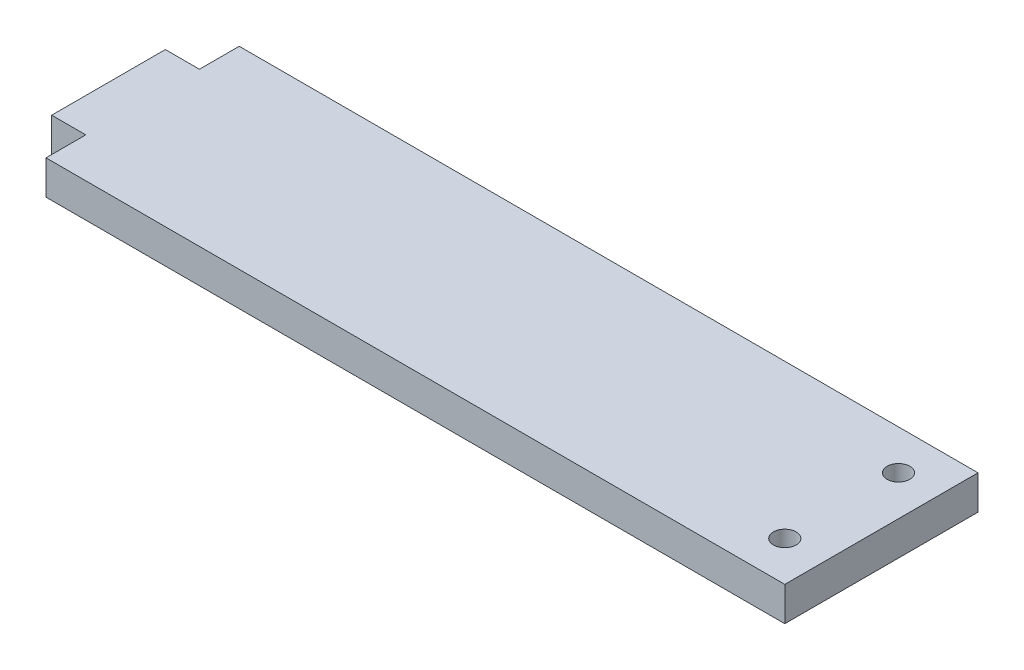
SolidWorks part; units mm, degrees
material "PVC rigide"
ref_plane "Plan de face" through (0, 0, 0) normal (0, 0, 1) x (1, 0, 0)
ref_plane "Plan de dessus" through (0, 0, 0) normal (0, 1, 0) x (1, 0, 0)
ref_plane "Plan de droite" through (0, 0, 0) normal (1, 0, 0) x (0, 0, -1)
sketch "Esquisse2" plane through (0, 0, 0) normal (0, 1, 0) x (1, 0, 0)
  line L0 (-353.8895, 0) -> (-217.8895, 0) construction
  line L1 (-347.8895, 17) -> (-217.8895, 17)
  line L2 (-353.8895, 10) -> (-353.8895, -10)
  line L3 (-282.8895, 17) -> (-282.8895, -17) construction
  line L4 (-347.8895, -10) -> (-347.8895, -17)
  line L5 (-353.8895, 10) -> (-347.8895, 10)
  line L6 (-353.8895, -10) -> (-347.8895, -10)
  line L7 (-347.8895, -17) -> (-217.8895, -17)
  line L8 (-347.8895, 10) -> (-347.8895, 17)
  line L9 (-217.8895, 17) -> (-217.8895, -17)
  point P0 (0, 0)
  point P11 (-282.8895, 0)
  dimension "D1" = 10
  dimension "D2" = 7
  dimension "D3" = 130
  dimension "D4" = 6
extrude "Boss.-Extru.1" add sketch "Esquisse2" along normal blind 6
sketch "Esquisse3" plane through (-347.8895, 0, 0) normal (-1, 0, 0) x (0, 0, 1)
  line L0 (-17, 3) -> (-10, 3) construction
  line L1 (-17, 6) -> (-17, 0) construction
  line L2 (-10, 6) -> (-10, 0) construction
  line L3 (10, 3) -> (17, 3) construction
  line L4 (10, 6) -> (10, 0) construction
  line L5 (17, 6) -> (17, 0) construction
  circle A0 centre (-13.5, 3) radius 2
  circle A1 centre (13.5, 3) radius 2
  dimension "D1" = 4
  dimension "D2" = 4
extrude "Enlèv. mat.-Extru.2" cut sketch "Esquisse3" against normal blind 10
sketch "Esquisse5" plane through (0, 6, 0) normal (0, 1, 0) x (1, 0, 0)
  line L0 (-217.8895, 17) -> (-347.8895, 17) construction
  line L1 (-217.8895, 0) -> (-353.8895, 0) construction
  line L2 (-217.8895, -17) -> (-217.8895, 17) construction
  line L3 (-353.8895, 10) -> (-353.8895, -10) construction
  circle A0 centre (-224.8895, 10) radius 2
  circle A1 centre (-224.8895, -10) radius 2
  dimension "D1" = 4
  dimension "D2" = 7
  dimension "D3" = 7
extrude "Enlèv. mat.-Extru.3" cut sketch "Esquisse5" against normal through all
